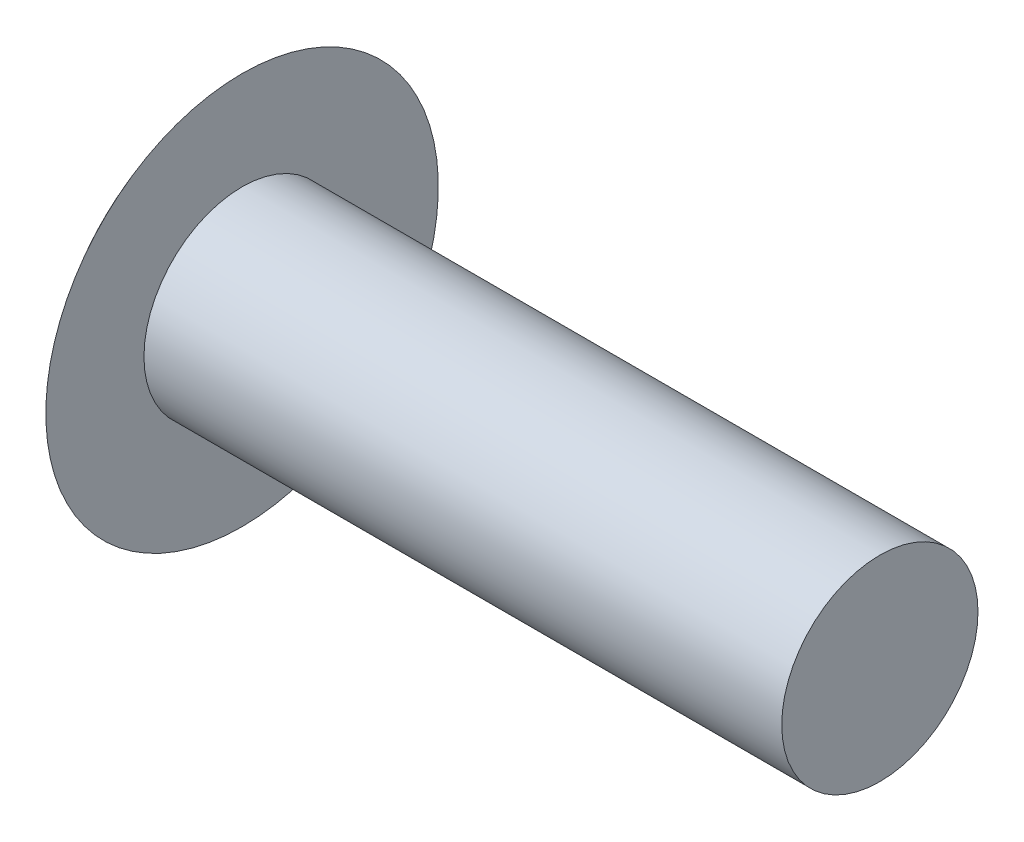
SolidWorks part; units mm, degrees
ref_plane "Front Plane" through (0, 0, 0) normal (0, 0, 1) x (1, 0, 0)
ref_plane "Top Plane" through (0, 0, 0) normal (0, 1, 0) x (1, 0, 0)
ref_plane "Right Plane" through (0, 0, 0) normal (1, 0, 0) x (0, 0, -1)
sketch "Sketch1" plane through (0, 0, 0) normal (1, 0, 0) x (0, 0, -1)
  circle A0 centre (0, 0) radius 2
  dimension "D1" = 4
extrude "Boss-Extrude1" add sketch "Sketch1" along normal blind 13
sketch "Sketch2" plane through (0, 0, 0) normal (0, 0, 1) x (1, 0, 0)
  line L0 (0, 0) -> (-3.0848, 0) construction
  line L1 (0, 0) -> (0, 4)
  line L2 (-1.357, 0) -> (-1.357, 3.5689) construction
  line L3 (-1.357, 0) -> (0, 0)
  arc A0 (0, 4) -> (-1.357, 0) centre (5.2169, 0) ccw
  point P6 (0, 3.5689)
  dimension "D1" = 4
revolve "Revolve1" add sketch "Sketch2" angle 360 about L3
